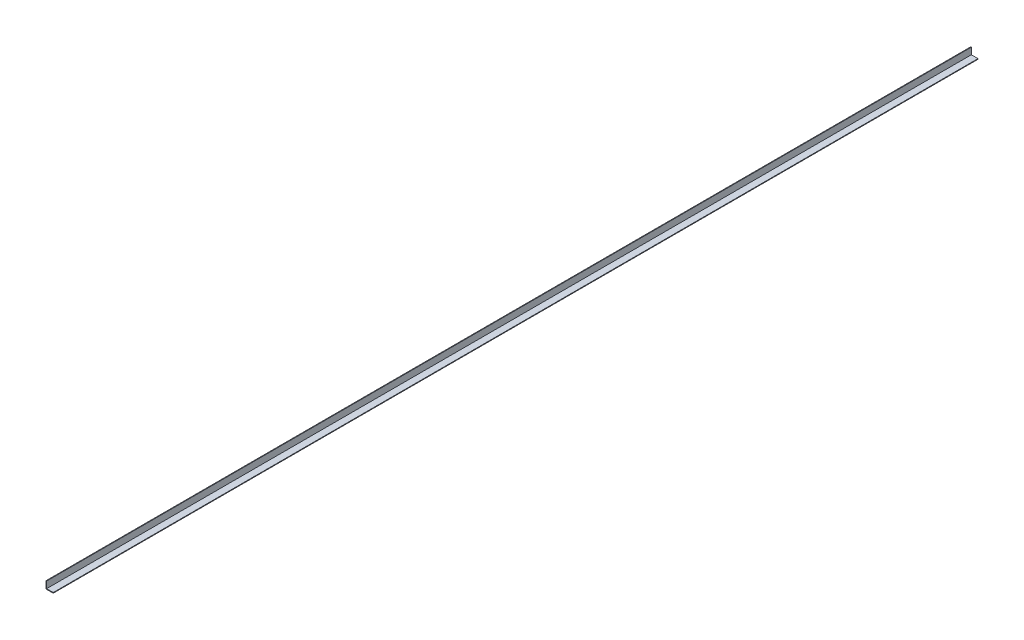
SolidWorks part; units mm, degrees
ref_plane "Front Plane" through (0, 0, 0) normal (0, 0, 1) x (1, 0, 0)
ref_plane "Top Plane" through (0, 0, 0) normal (0, 1, 0) x (1, 0, 0)
ref_plane "Right Plane" through (0, 0, 0) normal (1, 0, 0) x (0, 0, -1)
sketch "Sketch2" plane through (0, 0, 0) normal (0, 0, 1) x (1, 0, 0)
  line L0 (0, -9.525) -> (0, 9.525)
  line L1 (0, 9.525) -> (1.5875, 9.525)
  line L2 (1.5875, 9.525) -> (1.5875, -7.9375)
  line L3 (1.5875, -7.9375) -> (19.05, -7.9375)
  line L4 (19.05, -7.9375) -> (19.05, -9.525)
  line L5 (19.05, -9.525) -> (0, -9.525)
  point P4 (0, 0)
  dimension "D1" = 1.5875
  dimension "D2" = 1.5875
  dimension "D3" = 19.05
  dimension "D4" = 19.05
extrude "Boss-Extrude1" add sketch "Sketch2" along normal blind 2438.4
